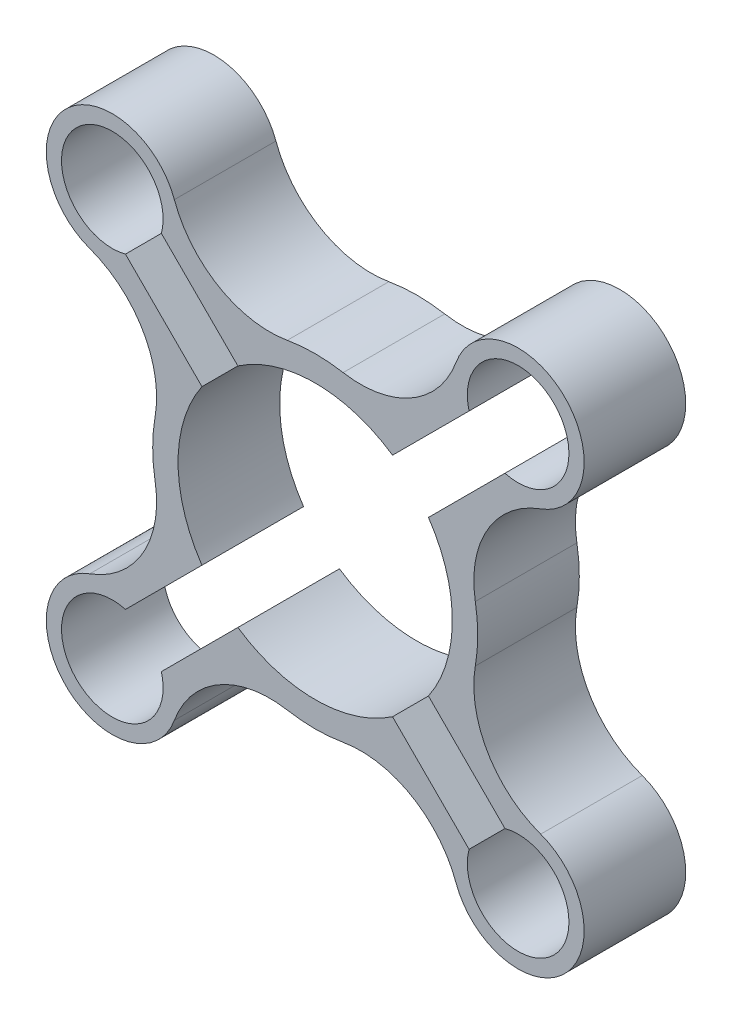
SolidWorks part; units mm, degrees
ref_plane "Front Plane" through (0, 0, 0) normal (0, 0, 1) x (1, 0, 0)
ref_plane "Top Plane" through (0, 0, 0) normal (0, 1, 0) x (1, 0, 0)
ref_plane "Right Plane" through (0, 0, 0) normal (1, 0, 0) x (0, 0, -1)
sketch "Sketch1" plane through (0, 0, 0) normal (0, 0, 1) x (1, 0, 0)
  line L0 (0, 0) -> (17831.8847, 0) construction
  line L1 (0, 0) -> (0, 17831.8847) construction
  line L2 (0, 0) -> (39.9515, 39.9515) construction
  line L3 (37.3633, 30.2923) -> (22.2972, 15.2261)
  line L4 (30.2923, 37.3633) -> (15.2261, 22.2972)
  line L5 (37.3633, -30.2923) -> (22.2972, -15.2261)
  line L6 (30.2923, -37.3633) -> (15.2261, -22.2972)
  line L7 (-30.2923, -37.3633) -> (-15.2261, -22.2972)
  line L8 (-37.3633, -30.2923) -> (-22.2972, -15.2261)
  line L9 (-37.3633, 30.2923) -> (-22.2972, 15.2261)
  line L10 (-30.2923, 37.3633) -> (-15.2261, 22.2972)
  arc A0 (15.2261, 22.2972) -> (-15.2261, 22.2972) centre (0, 0) ccw
  arc A1 (5.4999, 31.5238) -> (-5.4999, 31.5238) centre (0, 0) ccw
  circle A2 centre (0, 0) radius 56.5 construction
  arc A3 (37.3633, 30.2923) -> (30.2923, 37.3633) centre (39.9515, 39.9515) ccw
  arc A4 (44.3931, 27.7338) -> (27.7338, 44.3931) centre (39.9515, 39.9515) ccw
  arc A5 (27.7338, 44.3931) -> (5.4999, 31.5238) centre (8.9373, 51.2262) cw
  arc A6 (44.3931, 27.7338) -> (31.5238, 5.4999) centre (51.2262, 8.9373) ccw
  arc A7 (44.3931, -27.7338) -> (31.5238, -5.4999) centre (51.2262, -8.9373) cw
  arc A8 (27.7338, -44.3931) -> (44.3931, -27.7338) centre (39.9515, -39.9515) ccw
  arc A9 (30.2923, -37.3633) -> (37.3633, -30.2923) centre (39.9515, -39.9515) ccw
  arc A10 (27.7338, -44.3931) -> (5.4999, -31.5238) centre (8.9373, -51.2262) ccw
  arc A11 (-27.7338, -44.3931) -> (-5.4999, -31.5238) centre (-8.9373, -51.2262) cw
  arc A12 (-44.3931, -27.7338) -> (-27.7338, -44.3931) centre (-39.9515, -39.9515) ccw
  arc A13 (-37.3633, -30.2923) -> (-30.2923, -37.3633) centre (-39.9515, -39.9515) ccw
  arc A14 (-44.3931, -27.7338) -> (-31.5238, -5.4999) centre (-51.2262, -8.9373) ccw
  arc A15 (-44.3931, 27.7338) -> (-31.5238, 5.4999) centre (-51.2262, 8.9373) cw
  arc A16 (-27.7338, 44.3931) -> (-44.3931, 27.7338) centre (-39.9515, 39.9515) ccw
  arc A17 (-30.2923, 37.3633) -> (-37.3633, 30.2923) centre (-39.9515, 39.9515) ccw
  arc A18 (-27.7338, 44.3931) -> (-5.4999, 31.5238) centre (-8.9373, 51.2262) ccw
  arc A19 (-31.5238, 5.4999) -> (-31.5238, -5.4999) centre (0, 0) ccw
  arc A20 (-22.2972, 15.2261) -> (-22.2972, -15.2261) centre (0, 0) ccw
  arc A21 (-15.2261, -22.2972) -> (15.2261, -22.2972) centre (0, 0) ccw
  arc A22 (-5.4999, -31.5238) -> (5.4999, -31.5238) centre (0, 0) ccw
  arc A23 (31.5238, -5.4999) -> (31.5238, 5.4999) centre (0, 0) ccw
  arc A24 (22.2972, -15.2261) -> (22.2972, 15.2261) centre (0, 0) ccw
  point P6 (0, 0)
  point P7 (32, 0)
  point P54 (0, 0)
  dimension "D1" = 54
  dimension "D2" = 64
  dimension "D3" = 113
  dimension "D5" = 20
  dimension "D6" = 26
  dimension "D8" = 20
  dimension "D4" = 45
  dimension "D7" = 10
  dimension "D9" = 4
extrude "Boss-Extrude1" add sketch "Sketch1" along normal mid plane 20
